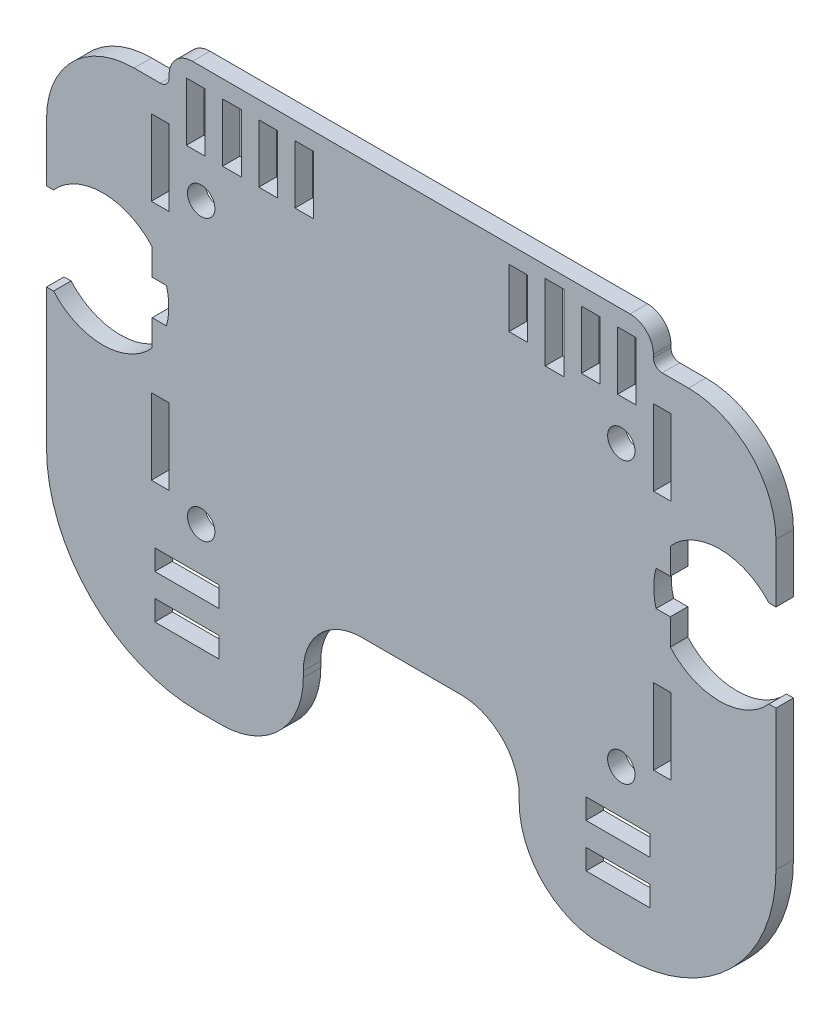
SolidWorks part; units mm, degrees
ref_plane "Přední rovina" through (0, 0, 0) normal (0, 0, 1) x (1, 0, 0)
ref_plane "Horní rovina" through (0, 0, 0) normal (0, 1, 0) x (1, 0, 0)
ref_plane "Pravá rovina" through (0, 0, 0) normal (1, 0, 0) x (0, 0, -1)
sketch "Skica2" plane through (0, 0, 0) normal (0, 0, 1) x (1, 0, 0)
  line L0 (-39.6595, 0) -> (1943.3131, 0) construction
  line L1 (0, -39.6595) -> (0, 1943.3131) construction
  line L2 (-62.5, 7.5) -> (-61.3, 7.5)
  line L3 (-44.3956, 7.5) -> (-44.3956, 3)
  line L4 (-44.3956, -3) -> (-44.3956, -7.5)
  line L5 (-61.3, -7.5) -> (-62.5, -7.5)
  line L6 (-41.5478, 14.2) -> (-41.5478, -3) construction
  line L8 (-62.5, 32.5) -> (-62.5, -16.7803) construction
  line L10 (62.5, 32.5) -> (62.5, -18.975) construction
  line L17 (-43.9478, -44.4435) -> (-32.9478, -44.4435)
  line L18 (-43.9478, -36.9445) -> (-32.9478, -36.9445)
  line L19 (-44.5478, -14.2) -> (-41.5478, -14.2)
  line L20 (-44.5478, 27.2) -> (-41.5478, 27.2)
  line L21 (-44.5478, 27.2) -> (-44.5478, 14.2)
  line L22 (-44.5478, 14.2) -> (-41.5478, 14.2)
  line L23 (-41.5478, 27.2) -> (-41.5478, 14.2)
  line L24 (-44.5478, -27.2) -> (-44.5478, -14.2)
  line L25 (-44.5478, -27.2) -> (-41.5478, -27.2)
  line L26 (-41.5478, -27.2) -> (-41.5478, -14.2)
  line L27 (-62.5, 7.5) -> (-62.5, 17.5)
  line L28 (-62.5, -7.5) -> (-62.5, -16.7803)
  line L29 (44.5478, -27.2) -> (41.5478, -27.2)
  line L30 (44.5478, -27.2) -> (44.5478, -14.2)
  line L31 (41.5478, -27.2) -> (41.5478, -14.2)
  line L32 (44.5478, -14.2) -> (41.5478, -14.2)
  line L33 (44.5478, 14.2) -> (41.5478, 14.2)
  line L34 (44.5478, 27.2) -> (41.5478, 27.2)
  line L35 (41.5478, 27.2) -> (41.5478, 14.2)
  line L36 (44.5478, 27.2) -> (44.5478, 14.2)
  line L41 (44.3956, -3) -> (44.3956, -7.5)
  line L42 (44.3956, 7.5) -> (44.3956, 3)
  line L43 (61.3, -7.5) -> (62.5, -7.5)
  line L44 (62.5, 7.5) -> (61.3, 7.5)
  line L45 (62.5, -7.5) -> (62.5, -18.975)
  line L46 (62.5, 7.5) -> (62.5, 17.5)
  line L47 (-44.3956, 3) -> (-41.9533, 3)
  line L48 (-44.3956, -3) -> (-41.9533, -3)
  line L49 (44.3956, -3) -> (41.9533, -3)
  line L50 (44.3956, 3) -> (41.9533, 3)
  line L51 (-8.5, -32.5) -> (8.5, -32.5)
  line L53 (-62.5, -16.7803) -> (-62.5, -31.5)
  line L57 (62.5, -18.975) -> (62.5, -31.5)
  line L60 (-43.9478, -36.9445) -> (-43.9478, -40.4435)
  line L61 (-43.9478, -40.4435) -> (-32.9478, -40.4435)
  line L62 (-32.9478, -36.9445) -> (-32.9478, -40.4435)
  line L63 (-43.9478, -44.4435) -> (-43.9478, -47.9425)
  line L64 (-43.9478, -47.9425) -> (-32.9478, -47.9425)
  line L65 (-32.9478, -44.4435) -> (-32.9478, -47.9425)
  line L71 (-38.5478, 35.5) -> (-35.3478, 35.5)
  line L72 (-38.5478, 35.5) -> (-38.5478, 25.5)
  line L73 (-38.5478, 25.5) -> (-35.3478, 25.5)
  line L74 (-35.3478, 35.5) -> (-35.3478, 25.5)
  line L78 (35.3478, 35.5) -> (38.5478, 35.5)
  line L79 (35.3478, 35.5) -> (35.3478, 25.5)
  line L80 (35.3478, 25.5) -> (38.5478, 25.5)
  line L81 (38.5478, 35.5) -> (38.5478, 25.5)
  line L82 (29.1478, 35.5) -> (32.3478, 35.5)
  line L83 (29.1478, 35.5) -> (29.1478, 25.5)
  line L84 (29.1478, 25.5) -> (32.3478, 25.5)
  line L85 (32.3478, 35.5) -> (32.3478, 25.5)
  line L90 (-43, 32.5) -> (-47.5, 32.5)
  line L92 (-41.5, 34) -> (-41.5, 34.5)
  line L93 (-37.5, 38.5) -> (37.5, 38.5)
  line L94 (41.5, 34) -> (41.5, 34.5)
  line L95 (43, 32.5) -> (47.5, 32.5)
  line L96 (22.9478, 36.5) -> (26.1478, 36.5)
  line L97 (22.9478, 36.5) -> (22.9478, 23.5)
  line L98 (22.9478, 23.5) -> (26.1478, 23.5)
  line L99 (26.1478, 36.5) -> (26.1478, 23.5)
  line L104 (29.9478, -36.9445) -> (40.9478, -36.9445)
  line L105 (29.9478, -36.9445) -> (29.9478, -40.4435)
  line L106 (29.9478, -40.4435) -> (40.9478, -40.4435)
  line L107 (40.9478, -36.9445) -> (40.9478, -40.4435)
  line L108 (-36.5, -57.5) -> (-32.5, -57.5)
  line L109 (-18.5, -43.5) -> (-18.5, -42.5)
  line L110 (36.5, -57.5) -> (32.5, -57.5)
  line L111 (18.5, -43.5) -> (18.5, -42.5)
  line L120 (-32.3478, 35.5) -> (-29.132, 35.5)
  line L121 (-32.3478, 35.5) -> (-32.3478, 25.5)
  line L122 (-32.3478, 25.5) -> (-29.132, 25.5)
  line L123 (-29.132, 35.5) -> (-29.132, 25.5)
  line L124 (-26.132, 35.5) -> (-22.932, 35.5)
  line L125 (-26.132, 35.5) -> (-26.132, 25.5)
  line L126 (-26.132, 25.5) -> (-22.932, 25.5)
  line L127 (-22.932, 35.5) -> (-22.932, 25.5)
  line L128 (-19.932, 35.5) -> (-16.732, 35.5)
  line L129 (-19.932, 35.5) -> (-19.932, 25.5)
  line L130 (-19.932, 25.5) -> (-16.732, 25.5)
  line L131 (-16.732, 35.5) -> (-16.732, 25.5)
  line L132 (16.7478, 35.5) -> (19.9478, 35.5)
  line L133 (16.7478, 35.5) -> (16.7478, 25.5)
  line L134 (16.7478, 25.5) -> (19.9478, 25.5)
  line L135 (19.9478, 35.5) -> (19.9478, 25.5)
  line L144 (29.9478, -44.4435) -> (40.9478, -44.4435)
  line L145 (29.9478, -44.4435) -> (29.9478, -47.9425)
  line L146 (29.9478, -47.9425) -> (40.9478, -47.9425)
  line L147 (40.9478, -44.4435) -> (40.9478, -47.9425)
  arc A0 (-44.3956, 7.5) -> (-61.3, 7.5) centre (-52.8478, 0) ccw
  arc A2 (-61.3, -7.5) -> (-44.3956, -7.5) centre (-52.8478, 0) ccw
  circle A3 centre (-52.8478, 0) radius 11.3 construction
  arc A5 (44.3956, 7.5) -> (61.3, 7.5) centre (52.8478, 0) cw
  arc A6 (61.3, -7.5) -> (44.3956, -7.5) centre (52.8478, 0) cw
  arc A19 (-41.9533, 3) -> (-41.9533, -3) centre (-52.8478, 0) cw
  arc A20 (41.9533, 3) -> (41.9533, -3) centre (52.8478, 0) ccw
  arc A21 (8.5, -32.5) -> (18.5, -42.5) centre (8.5, -42.5) cw
  arc A22 (-8.5, -32.5) -> (-18.5, -42.5) centre (-8.5, -42.5) ccw
  arc A25 (62.5, -31.5) -> (36.5, -57.5) centre (36.5, -31.5) cw
  arc A26 (-62.5, -31.5) -> (-36.5, -57.5) centre (-36.5, -31.5) ccw
  arc A27 (37.5, 38.5) -> (41.5, 34.5) centre (37.5, 34.5) cw
  arc A28 (-41.5, 34.5) -> (-37.5, 38.5) centre (-37.5, 34.5) cw
  arc A29 (47.5, 32.5) -> (62.5, 17.5) centre (47.5, 17.5) cw
  arc A30 (-47.5, 32.5) -> (-62.5, 17.5) centre (-47.5, 17.5) ccw
  arc A31 (43, 32.5) -> (41.5, 34) centre (43, 34) cw
  arc A32 (-43, 32.5) -> (-41.5, 34) centre (-43, 34) ccw
  arc A33 (-18.5, -43.5) -> (-32.5, -57.5) centre (-32.5, -43.5) cw
  arc A34 (32.5, -57.5) -> (18.5, -43.5) centre (32.5, -43.5) cw
  circle A35 centre (-36, 18.55) radius 2.35
  circle A36 centre (-36, -29.45) radius 2.35
  circle A38 centre (36, -29.45) radius 2.35
  circle A39 centre (36, 18.55) radius 2.35
  point P26 (0, 0)
  point P82 (-18.5, -57.5)
  point P94 (-18.5, -57.5)
  point P104 (-62.5, -57.5)
  point P107 (-19.932, 30.5)
  point P112 (30.7478, 35.5)
  point P117 (-41.5, 38.5)
  point P128 (-41.5, 32.5)
  point P138 (-22.932, 30.5)
  point P146 (0, 0)
  point P147 (0, 0)
  point P152 (0, 0)
  point P153 (0, 0)
  dimension "D1" = 22.6
  dimension "D2" = 6
  dimension "D17" = 3.2
  dimension "D19" = 3
  dimension "D23" = 10
  dimension "D24" = 14
  dimension "D34" = 4
  dimension "D35" = 15
  dimension "D36" = 1.5
  dimension "D21" = 14
  dimension "D65" = 29.45
  dimension "D67" = 36
  dimension "D73" = 18.55
  dimension "D3" = 15
  dimension "D4" = 1.2
  dimension "D5" = 125
  dimension "D7" = 3.499
  dimension "D8" = 11
  dimension "D9" = 3.2
  dimension "D10" = 13
  dimension "D11" = 3
  dimension "D12" = 14.2
  dimension "D13" = 10
  dimension "D14" = 3
  dimension "D15" = 3
  dimension "D16" = 3
  dimension "D18" = 3
  dimension "D20" = 3
  dimension "D22" = 44
  dimension "D25" = 3
  dimension "D26" = 21
  dimension "D27" = 21
  dimension "D28" = 10
  dimension "D29" = 10
  dimension "D30" = 3.2
  dimension "D31" = 3.2
  dimension "D32" = 3.2
  dimension "D33" = 6
  dimension "D37" = 13
  dimension "D38" = 2
  dimension "D39" = 0
  dimension "D40" = 4
  dimension "D41" = 0.6
  dimension "D42" = 0.6
  dimension "D43" = 36.6798
  dimension "D44" = 3.2
  dimension "D45" = 3
  dimension "D46" = 3.2
  dimension "D47" = 3
  dimension "D48" = 3
  dimension "D49" = 3
  dimension "D50" = 0
  dimension "D51" = 0
  dimension "D52" = 10
  dimension "D53" = 3
  dimension "D54" = 3
  dimension "D55" = 3
  dimension "D56" = 0
  dimension "D58" = 4
  dimension "D59" = 10
  dimension "D60" = 10
  dimension "D61" = 10
  dimension "D62" = 10
  dimension "D63" = 10
  dimension "D64" = 3.7
  dimension "D66" = 18.55
  dimension "D68" = 36
  dimension "D69" = 29.45
  dimension "D70" = 36
  dimension "D71" = 36
extrude "Přidat vysunutím1" add sketch "Skica2" along normal blind 3
